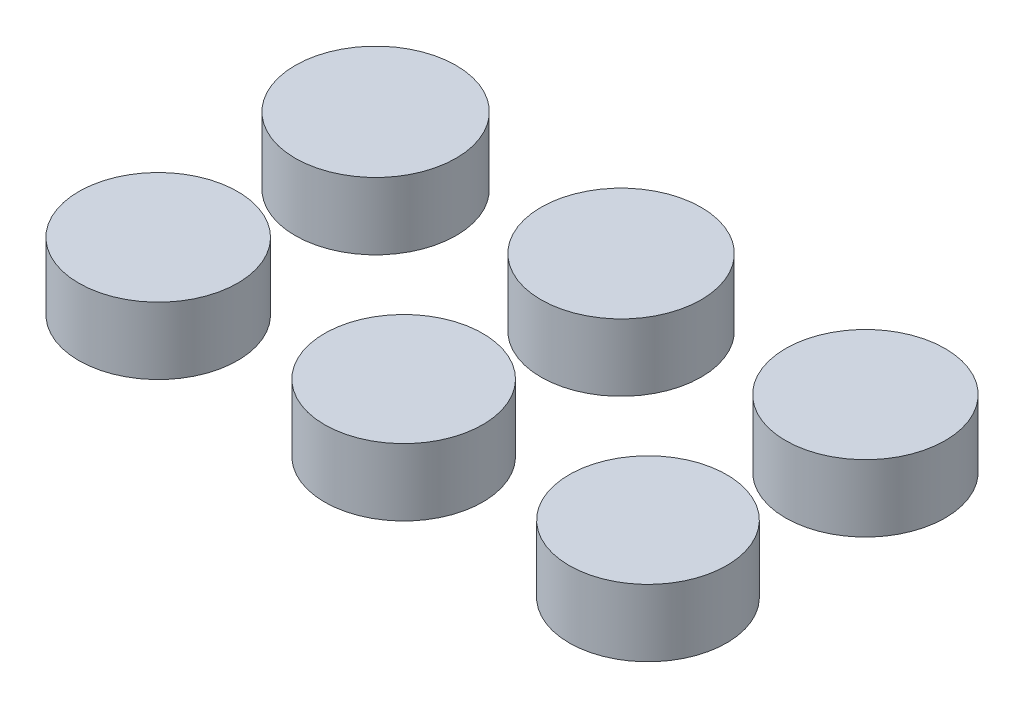
SolidWorks part; units mm, degrees
ref_plane "Front Plane" through (0, 0, 0) normal (0, 0, 1) x (1, 0, 0)
ref_plane "Top Plane" through (0, 0, 0) normal (0, 1, 0) x (1, 0, 0)
ref_plane "Right Plane" through (0, 0, 0) normal (1, 0, 0) x (0, 0, -1)
sketch "Sketch1" plane through (0, 0, 0) normal (0, 1, 0) x (1, 0, 0)
  circle A1 centre (0, 0) radius 6
  circle A12 centre (18.3075, 0) radius 5.975
  circle A13 centre (36.529, 0) radius 5.95
  circle A14 centre (36.529, -16.217) radius 5.875
  circle A15 centre (18.3075, -16.217) radius 5.9
  circle A16 centre (0, -16.217) radius 5.925
  point P1 (18.3075, 0)
  point P7 (36.529, 0)
  point P10 (0, -16.217)
  point P13 (18.3075, -16.217)
  point P16 (38.8718, -17.3884)
  point P17 (36.529, -16.217)
  dimension "D1" = 12
  dimension "D5" = 11.95
  dimension "D6" = 11.9
  dimension "D7" = 11.85
  dimension "D8" = 11.8
  dimension "D9" = 11.75
extrude "Boss-Extrude1" add sketch "Sketch1" along normal blind 5
